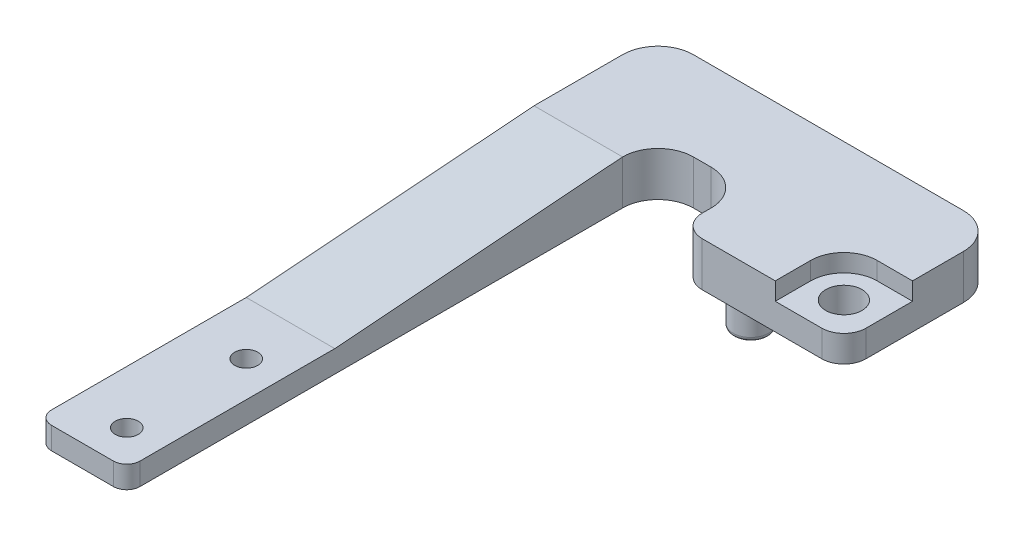
SolidWorks part; units mm, degrees
ref_plane "Front Plane" through (0, 0, 0) normal (0, 0, 1) x (1, 0, 0)
ref_plane "Top Plane" through (0, 0, 0) normal (0, 1, 0) x (1, 0, 0)
ref_plane "Right Plane" through (0, 0, 0) normal (1, 0, 0) x (0, 0, -1)
sketch "Sketch1" plane through (0, 0, 0) normal (0, 1, 0) x (1, 0, 0)
  line L12 (28.8534, 9.2067) -> (1.8534, 9.2067)
  line L13 (33.8534, 14.2067) -> (33.8534, 36.2067)
  line L14 (25.8534, 44.2067) -> (-3.1466, 44.2067)
  line L24 (-3.1466, 14.2067) -> (-3.1466, 16.2067)
  line L25 (-3.1466, 44.2067) -> (-35.1466, 44.2067)
  line L27 (-11.1466, 24.2067) -> (-15.1466, 24.2067)
  line L28 (-43.1466, 36.2067) -> (-43.1466, 4.2067)
  line L30 (-43.1466, 4.2067) -> (-43.1466, -92.7933)
  line L31 (-40.1466, -95.7933) -> (-26.1466, -95.7933)
  line L32 (-23.1466, 16.2067) -> (-23.1466, -92.7933)
  circle A0 centre (25.8534, 17.2067) radius 4.1
  circle A1 centre (4.8534, 17.2067) radius 4
  arc A25 (-15.1466, 24.2067) -> (-23.1466, 16.2067) centre (-15.1466, 16.2067) ccw
  arc A26 (-3.1466, 16.2067) -> (-11.1466, 24.2067) centre (-11.1466, 16.2067) ccw
  arc A27 (28.8534, 9.2067) -> (33.8534, 14.2067) centre (28.8534, 14.2067) ccw
  arc A28 (1.8534, 9.2067) -> (-3.1466, 14.2067) centre (1.8534, 14.2067) cw
  arc A29 (33.8534, 36.2067) -> (25.8534, 44.2067) centre (25.8534, 36.2067) ccw
  arc A30 (-35.1466, 44.2067) -> (-43.1466, 36.2067) centre (-35.1466, 36.2067) ccw
  arc A31 (-26.1466, -95.7933) -> (-23.1466, -92.7933) centre (-26.1466, -92.7933) ccw
  arc A32 (-43.1466, -92.7933) -> (-40.1466, -95.7933) centre (-40.1466, -92.7933) ccw
  circle A33 centre (-31.1466, -87.7933) radius 2.6
  circle A34 centre (-31.1466, -60.7933) radius 2.6
  dimension "D1" = 21
  dimension "D9" = 15
  dimension "D13" = 8
  dimension "D14" = 3
  dimension "D15" = 27
  dimension "D16" = 8
  dimension "D2" = 8
  dimension "D11" = 8
  dimension "D12" = 5
  dimension "D3" = 8
  dimension "D4" = 8
  dimension "D5" = 77
  dimension "D6" = 35
  dimension "D7" = 8
  dimension "D8" = 20
  dimension "D10" = 140
  dimension "D17" = 8
  dimension "D18" = 8
extrude "Boss-Extrude1" add sketch "Sketch1" along normal blind 10
sketch "Sketch2" plane through (0, 10, 0) normal (0, 1, 0) x (1, 0, 0)
  line L0 (25.8534, 24.7067) -> (33.8534, 24.7067)
  line L1 (33.8534, 14.2067) -> (33.8534, 36.2067) construction
  line L2 (33.8534, 24.7067) -> (33.8534, 14.2067)
  line L3 (18.3534, 17.2067) -> (18.3534, 9.2067)
  line L4 (1.8534, 9.2067) -> (28.8534, 9.2067) construction
  line L5 (18.3534, 9.2067) -> (28.8534, 9.2067)
  arc A0 (25.8534, 24.7067) -> (18.3534, 17.2067) centre (25.8534, 17.2067) ccw
  arc A1 (28.8534, 9.2067) -> (33.8534, 14.2067) centre (28.8534, 14.2067) ccw
extrude "Cut-Extrude1" cut sketch "Sketch2" against normal blind 4
sketch "Sketch3" plane through (-23.1466, 0, 0) normal (1, 0, 0) x (0, 0, -1)
  line L0 (16.2067, 10) -> (-48.7933, 5)
  line L1 (-48.7933, 5) -> (-99.9817, 5)
  line L2 (-99.9817, 5) -> (-99.9817, 10)
  line L3 (-99.9817, 10) -> (16.2067, 10)
  line L4 (16.2067, 10) -> (16.2067, 0) construction
  dimension "D1" = 5
  dimension "D2" = 65
extrude "Cut-Extrude2" cut sketch "Sketch3" against normal up to surface (20 mm away) up to face at (-43.1466, 5, 28.2933)
sketch "Sketch5" plane through (0, 0, 0) normal (0, -1, 0) x (-1, 0, 0)
  circle A0 centre (-4.8534, 17.2067) radius 4
extrude "Boss-Extrude2" add sketch "Sketch5" along normal blind 10 and the other way up to surface (10 mm away) other way up to face at (-1.4525, 10, -24.2831)
fillet "Fillet1" radius 1 2 edges at (4.8534, -10, -21.2067) (4.8534, 0, -13.2067)
